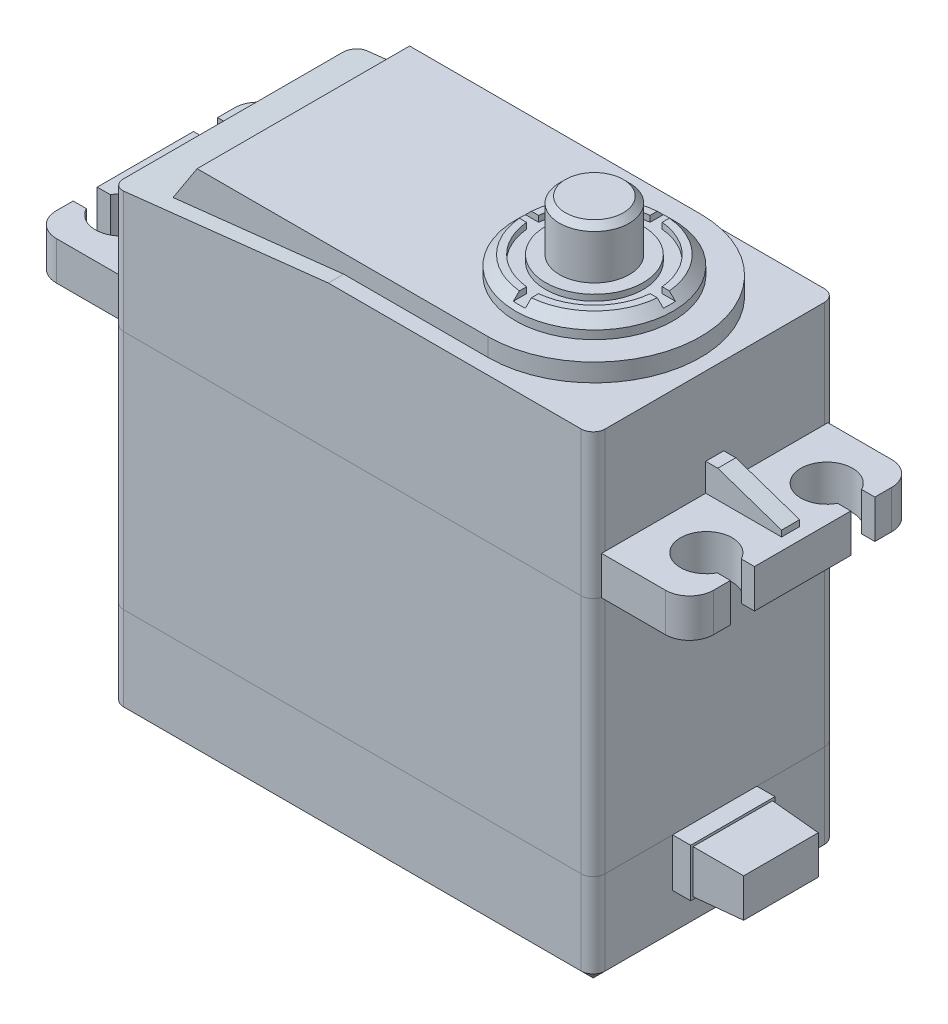
SolidWorks part; units mm, degrees
ref_plane "Front Plane" through (0, 0, 0) normal (0, 0, 1) x (1, 0, 0)
ref_plane "Top Plane" through (0, 0, 0) normal (0, 1, 0) x (1, 0, 0)
ref_plane "Right Plane" through (0, 0, 0) normal (1, 0, 0) x (0, 0, -1)
sketch "Sketch1" plane through (0, 0, 0) normal (0, 1, 0) x (1, 0, 0)
  line L1 (0, 0) -> (40, 0)
  line L2 (0, 0) -> (0, 20.2)
  line L3 (0, 20.2) -> (40, 20.2)
  line L4 (40, 0) -> (40, 20.2)
  dimension "D1" = 40
  dimension "D2" = 20.2
extrude "Boss-Extrude1" add sketch "Sketch1" along normal blind 8
sketch "Sketch3" plane through (0, 8, 0) normal (0, 1, 0) x (1, 0, 0)
  line L1 (0, 20.2) -> (40, 20.2)
  line L2 (0, 20.2) -> (0, 0)
  line L3 (0, 0) -> (40, 0)
  line L4 (40, 20.2) -> (40, 0)
extrude "Boss-Extrude2" add sketch "Sketch3" along normal blind 20 separate body
sketch "Sketch4" plane through (0, 28, 0) normal (0, 1, 0) x (1, 0, 0)
  line L1 (0, 0) -> (40, 0)
  line L2 (0, 0) -> (0, 20.2)
  line L3 (0, 20.2) -> (40, 20.2)
  line L4 (40, 0) -> (40, 20.2)
extrude "Boss-Extrude5" add sketch "Sketch4" along normal blind 12 separate body
sketch "Sketch5" plane through (0, 0, 0) normal (0, 0, 1) x (1, 0, 0)
  line L0 (0, 38) -> (18, 40)
  line L1 (18, 40) -> (0, 40)
  line L2 (0, 40) -> (0, 38)
  line L3 (0, 40) -> (0, 28) construction
  line L4 (0, 40) -> (40, 40) construction
  dimension "D1" = 18
  dimension "D2" = 2
extrude "Cut-Extrude1" cut sketch "Sketch5" against normal through all
ref_plane "Plane1" through (0, 28, 0) normal (0, -1, 0) x (-1, 0, 0)
sketch "Sketch6" plane through (0, 28, 0) normal (0, -1, 0) x (-1, 0, 0)
  line L0 (0, 20.2) -> (0, 0) construction
  line L1 (0, 19.5) -> (7.3, 19.5)
  line L2 (0, 19.5) -> (0, 0.7)
  line L3 (0, 0.7) -> (7.3, 0.7)
  line L4 (7.3, 19.5) -> (7.3, 0.7)
  line L7 (0, 10.1) -> (7.3, 10.1) construction
  line L8 (-40, 0) -> (-40, 20.2) construction
  line L9 (-40, 19.5) -> (-47.3, 19.5)
  line L10 (-40, 19.5) -> (-40, 0.7)
  line L11 (-40, 0.7) -> (-47.3, 0.7)
  line L12 (-47.3, 19.5) -> (-47.3, 0.7)
  dimension "D1" = 7.3
  dimension "D2" = 18.8
  dimension "D3" = 7.3
extrude "Boss-Extrude6" add sketch "Sketch6" against normal blind 3.2 separate body
sketch "Sketch7" plane through (0, 31.2, 0) normal (0, 1, 0) x (1, 0, 0)
  line L0 (-7.3, 10.1) -> (0, 10.1) construction
  line L1 (-7.3, 0.7) -> (-7.3, 19.5) construction
  line L2 (0, 20.2) -> (0, 0) construction
  line L3 (-4.3, 15.1) -> (-4.3, 5.1) construction
  line L4 (-6.2033, 4.1) -> (-7.3, 4.1)
  line L5 (-7.3, 4.1) -> (-7.3, 6.1)
  line L6 (-7.3, 6.1) -> (-6.2033, 6.1)
  line L7 (-6.2033, 14.1) -> (-7.3, 14.1)
  line L8 (-7.3, 14.1) -> (-7.3, 16.1)
  line L9 (-7.3, 16.1) -> (-6.2033, 16.1)
  line L10 (44.3, 15.1) -> (44.3, 5.1) construction
  line L11 (46.2033, 6.1) -> (47.3, 6.1)
  line L12 (47.3, 6.1) -> (47.3, 4.1)
  line L13 (47.3, 4.1) -> (46.2033, 4.1)
  line L14 (46.2033, 16.1) -> (47.3, 16.1)
  line L15 (47.3, 16.1) -> (47.3, 14.1)
  line L16 (47.3, 14.1) -> (46.2033, 14.1)
  line L17 (47.3, 19.5) -> (47.3, 0.7) construction
  arc A0 (-6.2033, 14.1) -> (-6.2033, 16.1) centre (-4.3, 15.1) ccw
  arc A1 (-6.2033, 4.1) -> (-6.2033, 6.1) centre (-4.3, 5.1) ccw
  arc A2 (46.2033, 16.1) -> (46.2033, 14.1) centre (44.3, 15.1) ccw
  arc A3 (46.2033, 6.1) -> (46.2033, 4.1) centre (44.3, 5.1) ccw
  point P8 (-4.3, 10.1)
  point P20 (-7.3, 15.1)
  point P21 (-7.3, 5.1)
  point P23 (44.3, 10.1)
  point P24 (-3.65, 10.1)
  point P35 (47.3, 5.1)
  point P37 (47.3, 15.1)
  dimension "D1" = 4.3
  dimension "D2" = 4.3
  dimension "D7" = 10
  dimension "D8" = 4.3
  dimension "D9" = 4.3
  dimension "D3" = 10
  dimension "D4" = 3
  dimension "D5" = 2
  dimension "D6" = 2
  dimension "D10" = 2
  dimension "D11" = 2
  dimension "D12" = 3
extrude "Cut-Extrude2" cut sketch "Sketch7" against normal through all
ref_plane "Plane2" through (0, 0, -10.1) normal (0, 0, 1) x (1, 0, 0)
sketch "Sketch8" plane through (0, 0, -10.1) normal (0, 0, 1) x (1, 0, 0)
  line L0 (-6.3, 31.2) -> (0, 31.2)
  line L1 (0, 31.2) -> (0, 33.5)
  line L2 (0, 33.5) -> (-1, 33.5)
  line L3 (-1, 33.5) -> (-6.3, 31.7)
  line L4 (-6.3, 31.7) -> (-6.3, 31.2)
  line L5 (0, 31.2) -> (-7.3, 31.2) construction
  line L6 (0, 38) -> (0, 28) construction
  line L7 (-7.3, 31.2) -> (-7.3, 28) construction
  dimension "D1" = 1
  dimension "D2" = 1
  dimension "D3" = 0.5
  dimension "D4" = 2.3
extrude "Boss-Extrude7" add sketch "Sketch8" along normal mid plane 1.5
fillet "Fillet1" radius 2 2 edges at (-7.3, 29.6, -19.5) (-7.3, 29.6, -0.7)
ref_plane "Plane3" through (20, 0, 0) normal (-1, 0, 0) x (0, 0, 1)
mirror "Mirror12" about plane through (20, 0, 0) normal (-1, 0, 0) of "Boss-Extrude7"
fillet "Fillet3" radius 2 2 edges at (47.3, 29.6, -19.5) (47.3, 29.6, -0.7)
sketch "Sketch9" plane through (0, 40, 0) normal (0, 1, 0) x (1, 0, 0)
  line L0 (-6.6, 10.1) -> (6.6, 10.1) construction
  line L1 (30, 18.925) -> (5.825, 18.925)
  line L3 (30, 1.275) -> (5.825, 1.275)
  line L4 (5.825, 18.925) -> (5.825, 1.275)
  line L5 (40, 0.7) -> (40, 19.5) construction
  arc A0 (30, 1.275) -> (30, 18.925) centre (30, 10.1) ccw
  point P11 (38.825, 10.1)
  dimension "D1" = 17.65
  dimension "D2" = 10
  dimension "D3" = 33
extrude "Boss-Extrude8" add sketch "Sketch9" along normal blind 1.5 and the other way up to next
sketch "Sketch10" plane through (0, 0, -1.275) normal (0, 0, 1) x (1, 0, 0)
  line L0 (5.825, 41.5) -> (3.825, 38.425)
  line L1 (3.825, 38.425) -> (5.825, 38.6472)
  line L2 (5.825, 38.6472) -> (5.825, 41.5)
  line L3 (0, 38) -> (18, 40) construction
  dimension "D1" = 2
extrude "Boss-Extrude9" add sketch "Sketch10" against normal up to surface (17.65 mm away) up to face at (17.93, 40.3294, -18.925)
sketch "Sketch11" plane through (0, 41.5, 0) normal (0, 1, 0) x (1, 0, 0)
  circle A0 centre (30, 10.1) radius 6.55
  arc A1 (30, 1.275) -> (30, 18.925) centre (30, 10.1) ccw construction
  dimension "D1" = 13.1
extrude "Boss-Extrude10" add sketch "Sketch11" along normal blind 1.5
chamfer "Chamfer1" distance 0.8 1 edges at (30, 43, -3.55)
sketch "Sketch12" plane through (0, 43, 0) normal (0, 1, 0) x (1, 0, 0)
  line L2 (29.5, 15.2332) -> (29.5, 16.6309)
  line L4 (30.5, 15.2332) -> (30.5, 16.6309)
  line L5 (35.1332, 10.6) -> (36.5309, 10.6)
  line L7 (35.1332, 9.6) -> (36.5309, 9.6)
  line L10 (30.5, 4.9668) -> (30.5, 3.5691)
  line L12 (29.5, 4.9668) -> (29.5, 3.5691)
  line L13 (24.8668, 10.6) -> (23.4691, 10.6)
  line L15 (24.8668, 9.6) -> (23.4691, 9.6)
  line L17 (30, 14.15) -> (30, 6.05) construction
  line L18 (34.05, 10.1) -> (25.95, 10.1) construction
  circle A0 centre (30, 10.1) radius 4.05
  circle A1 centre (30, 10.1) radius 5.75 construction
  arc A2 (24.8668, 9.6) -> (29.5, 4.9668) centre (30, 10.1) ccw
  arc A3 (30.5, 4.9668) -> (35.1332, 9.6) centre (30, 10.1) ccw
  arc A4 (35.1332, 10.6) -> (30.5, 15.2332) centre (30, 10.1) ccw
  arc A5 (29.5, 15.2332) -> (24.8668, 10.6) centre (30, 10.1) ccw
  arc A6 (29.5, 3.5691) -> (30.5, 3.5691) centre (30, 10.1) ccw
  circle A7 centre (30, 10.1) radius 6.55 construction
  arc A8 (23.4691, 9.6) -> (23.4691, 10.6) centre (30, 10.1) cw
  arc A9 (29.5, 16.6309) -> (30.5, 16.6309) centre (30, 10.1) cw
  arc A10 (36.5309, 9.6) -> (36.5309, 10.6) centre (30, 10.1) ccw
  circle A11 centre (30, 10.1) radius 6.55 construction
  dimension "D1" = 8.1
  dimension "D2" = 5.1575
  dimension "D4" = 1
  dimension "D3" = 1
  dimension "D5" = 1
  dimension "D6" = 1
extrude "Cut-Extrude3" cut sketch "Sketch12" against normal blind 0.5
sketch "Sketch13" plane through (0, 43, 0) normal (0, 1, 0) x (1, 0, 0)
  circle A0 centre (30, 10.1) radius 2.9
  circle A1 centre (30, 10.1) radius 4.05 construction
  dimension "D1" = 5.8
extrude "Boss-Extrude11" add sketch "Sketch13" along normal blind 4.2
chamfer "Chamfer2" distance 0.5 1 edges at (30, 47.2, -7.2)
fillet "Fillet4" radius 1 4 edges at (0, 33, -20.2) (40, 34, -20.2) (40, 34, 0) (0, 33, 0)
fillet "Fillet5" radius 1 4 edges at (0, 4, 0) (0, 4, -20.2) (40, 4, 0) (40, 4, -20.2)
fillet "Fillet6" radius 1 4 edges at (40, 18, -20.2) (40, 18, 0) (0, 18, -20.2) (0, 18, 0)
chamfer "Chamfer3" distance 1 8 edges at (0, 0, -10.1) (20, 0, 0) (20, 0, -20.2) (0.2929, 0, -0.2929) (0.2929, 0, -19.9071) (39.7071, 0, -0.2929) (39.7071, 0, -19.9071) (40, 0, -10.1)
sketch "Sketch14" plane through (40, 0, 0) normal (1, 0, 0) x (0, 0, -1)
  line L0 (1, 8) -> (19.2, 8) construction
  line L1 (6.6, 8) -> (13.6, 8)
  line L2 (6.6, 8) -> (6.6, 4)
  line L3 (6.6, 4) -> (13.6, 4)
  line L4 (13.6, 8) -> (13.6, 4)
  point P6 (10.1, 8)
  point P7 (10.1, 8)
  dimension "D1" = 7
  dimension "D2" = 4
extrude "Boss-Extrude13" add sketch "Sketch14" along normal blind 1.5 separate body
sketch "Sketch15" plane through (41.5, 0, 0) normal (1, 0, 0) x (0, 0, -1)
  line L8 (6.8, 7.8) -> (6.8, 4.2)
  line L9 (6.8, 4.2) -> (13.4, 4.2)
  line L10 (13.4, 4.2) -> (13.4, 7.8)
  line L11 (13.4, 7.8) -> (6.8, 7.8)
  line L12 (6.8, 7.8) -> (6.8, 4.2)
  line L13 (6.8, 4.2) -> (13.4, 4.2)
  line L14 (13.4, 4.2) -> (13.4, 7.8)
  line L15 (13.4, 7.8) -> (6.8, 7.8)
  dimension "D1" = 0.2
ref_plane "Plane4" through (45.5, 0, 0) normal (1, 0, 0) x (0, 0, -1)
sketch "Sketch16" plane through (45.5, 0, 0) normal (1, 0, 0) x (0, 0, -1)
  line L8 (7, 7.6) -> (7, 4.4)
  line L9 (7, 4.4) -> (13.2, 4.4)
  line L10 (13.2, 4.4) -> (13.2, 7.6)
  line L11 (13.2, 7.6) -> (7, 7.6)
  line L12 (7, 7.6) -> (7, 4.4)
  line L13 (7, 4.4) -> (13.2, 4.4)
  line L14 (13.2, 4.4) -> (13.2, 7.6)
  line L15 (13.2, 7.6) -> (7, 7.6)
  dimension "D1" = 0.4
loft "Loft1" add profiles "Sketch15", "Sketch16"
